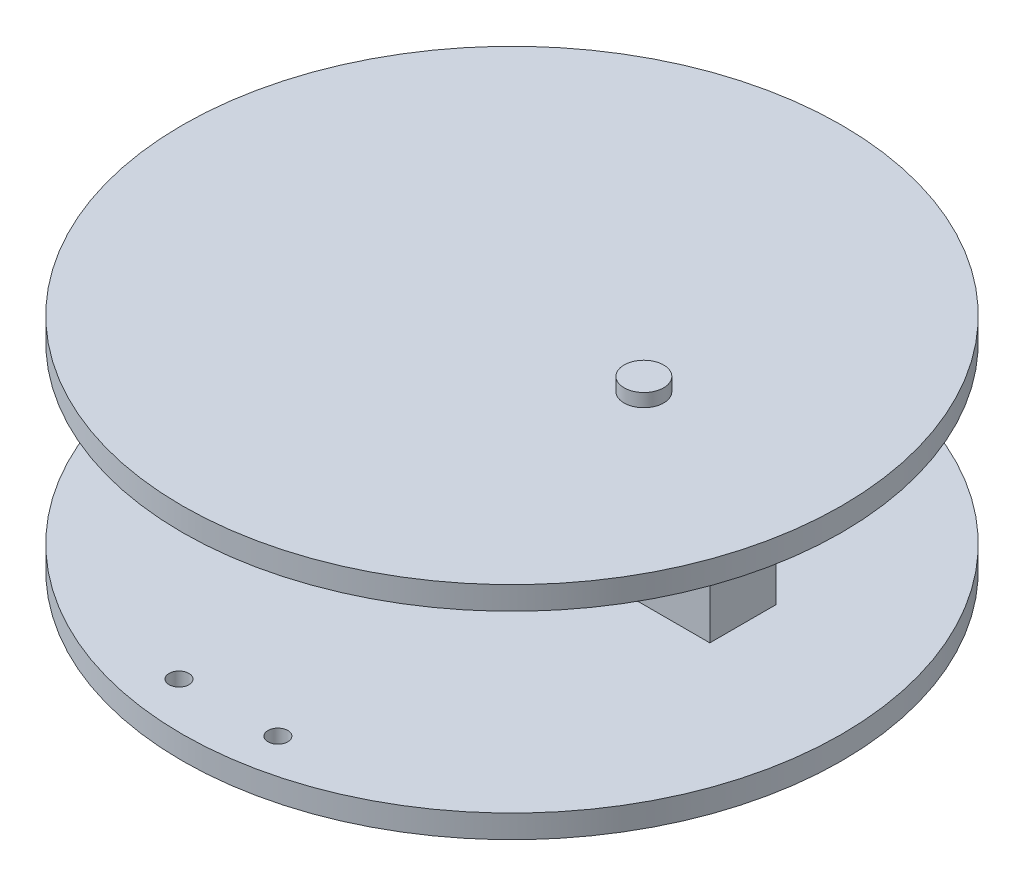
SolidWorks part; units mm, degrees
ref_plane "前视基准面" through (0, 0, 0) normal (0, 0, 1) x (1, 0, 0)
ref_plane "上视基准面" through (0, 0, 0) normal (0, 1, 0) x (1, 0, 0)
ref_plane "右视基准面" through (0, 0, 0) normal (1, 0, 0) x (0, 0, -1)
sketch "草图1" plane through (0, 0, 0) normal (0, 1, 0) x (1, 0, 0)
  circle A0 centre (0, 0) radius 50
  dimension "D1" = 100
extrude "凸台-拉伸1" add sketch "草图1" along normal blind 3.5
pattern_linear "阵列(线性)3" count 2 spacing 30 along (0, 1, 0) of "凸台-拉伸1"
sketch "草图2" plane through (0, 0, 0) normal (0, 1, 0) x (1, 0, 0)
  line L1 (-35, -5) -> (35, -5)
  line L2 (-35, -5) -> (-35, 5)
  line L3 (-35, 5) -> (35, 5)
  line L4 (35, -5) -> (35, 5)
  line L5 (-35, -5) -> (35, 5) construction
  line L6 (-35, 5) -> (35, -5) construction
  point P1 (0, 0)
  dimension "D1" = 10
  dimension "D2" = 70
extrude "凸台-拉伸2" add sketch "草图2" along normal blind 10 from offset 10.5 separate body
sketch "草图3" plane through (0, 33.5, 0) normal (0, 1, 0) x (1, 0, 0)
  circle A0 centre (20, 0) radius 3
  dimension "D2" = 6
  dimension "D1" = 20
extrude "凸台-拉伸3" add sketch "草图3" along normal blind 2
sketch "草图5" plane through (0, 3.5, 0) normal (0, 1, 0) x (1, 0, 0)
  line L0 (0, 0) -> (0, -66.8244) construction
  line L1 (-11.2494, 0) -> (26.2158, 0) construction
  circle A0 centre (-7.5, -43) radius 1.5
  circle A2 centre (7.5, -43) radius 1.5
  dimension "D1" = 3
  dimension "D2" = 43
  dimension "D3" = 15
extrude "切除-拉伸1" cut sketch "草图5" against normal through all
sketch "草图6" plane through (0, 0, 0) normal (0, -1, 0) x (1, 0, 0)
  circle A0 centre (0, 0) radius 39 construction
  circle A1 centre (0, -39) radius 3
  circle A2 centre (-33.775, 19.5) radius 3
  circle A3 centre (33.775, 19.5) radius 3
  dimension "D1" = 78
  dimension "D2" = 6
  dimension "D3" = 3
extrude "凸台-拉伸4" add sketch "草图6" along normal blind 3
